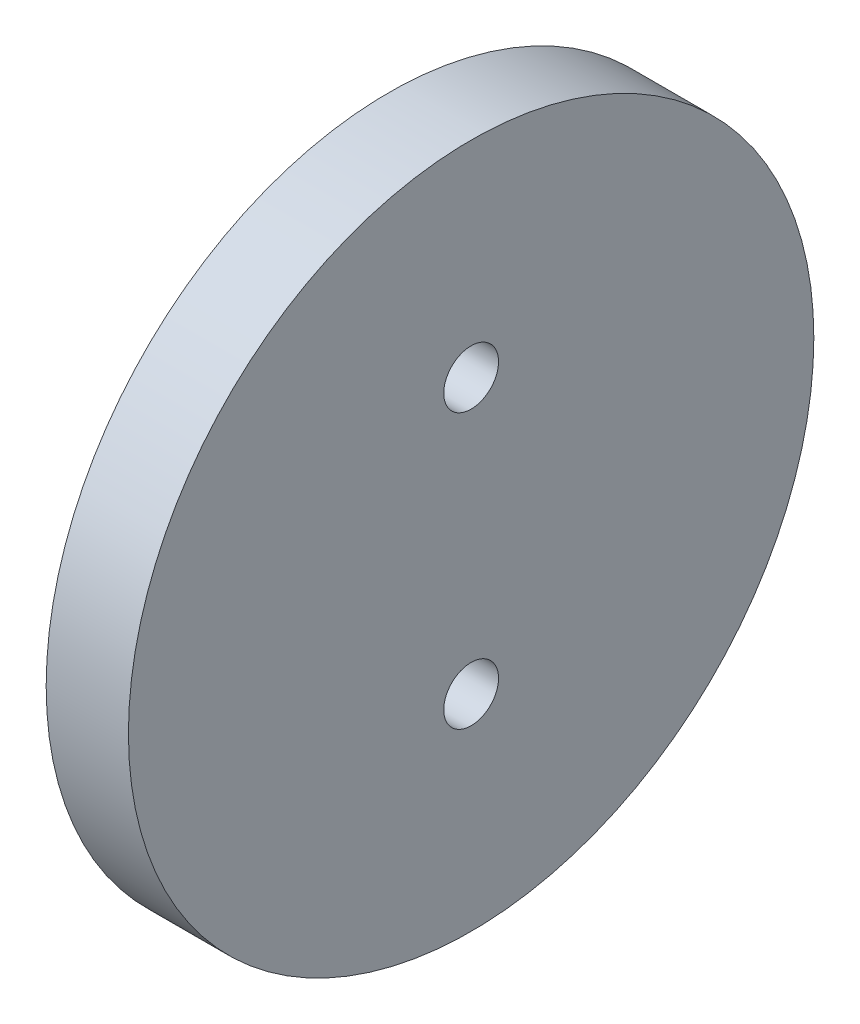
SolidWorks part; units mm, degrees
ref_plane "前视基准面" through (0, 0, 0) normal (0, 0, 1) x (1, 0, 0)
ref_plane "上视基准面" through (0, 0, 0) normal (0, 1, 0) x (1, 0, 0)
ref_plane "右视基准面" through (0, 0, 0) normal (1, 0, 0) x (0, 0, -1)
other "Configuration Table"
sketch "草图1" plane through (0, 0, 0) normal (1, 0, 0) x (0, 0, -1)
  circle A0 centre (0, 0) radius 12.5
  dimension "D1" = 25
extrude "凸台-拉伸1" add sketch "草图1" along normal blind 3
sketch "草图2" plane through (3, 0, 0) normal (1, 0, 0) x (0, 0, -1)
  line L0 (0, 0) -> (0, 10) construction
  circle A0 centre (0, 5) radius 1
  circle A1 centre (0, -5) radius 1
  dimension "D3" = 2
  dimension "D4" = 2
  dimension "D1" = 10
  dimension "D2" = 5
extrude "切除-拉伸1" cut sketch "草图2" against normal blind 3
